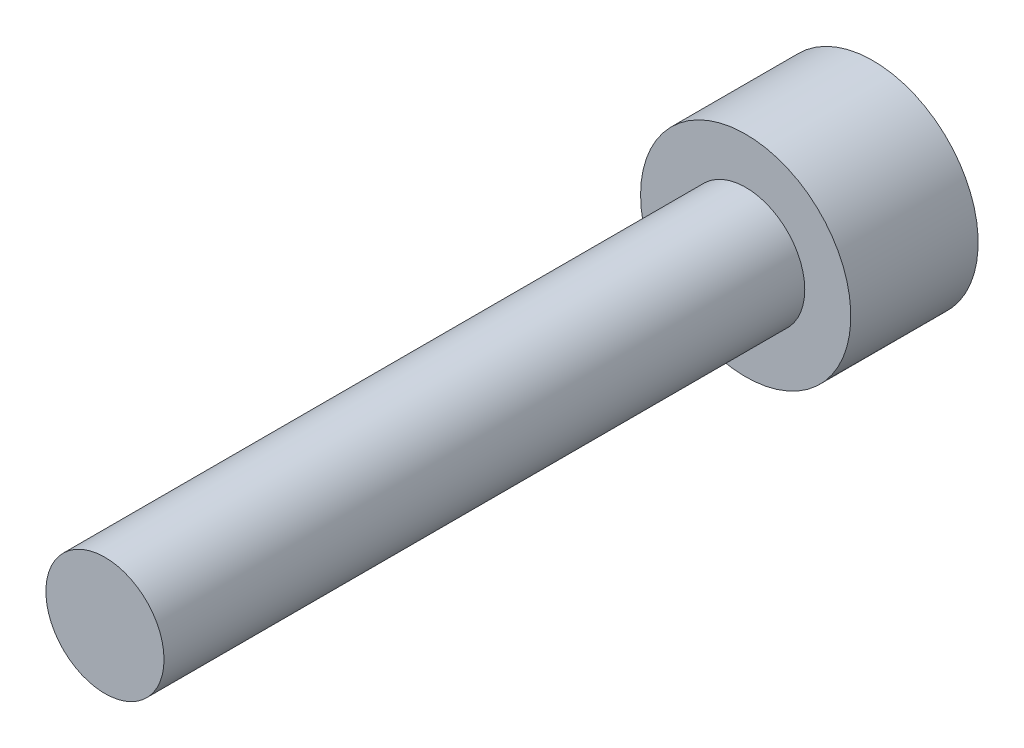
SolidWorks part; units mm, degrees
ref_plane "Front Plane" through (0, 0, 0) normal (0, 0, 1) x (1, 0, 0)
ref_plane "Top Plane" through (0, 0, 0) normal (0, 1, 0) x (1, 0, 0)
ref_plane "Right Plane" through (0, 0, 0) normal (1, 0, 0) x (0, 0, -1)
sketch "Sketch1" plane through (0, 0, 0) normal (0, 0, 1) x (1, 0, 0)
  circle A0 centre (0, 0) radius 2.625
  dimension "D1" = 5.25
extrude "Boss-Extrude1" add sketch "Sketch1" along normal blind 3.18 contours A0
sketch "Sketch2" plane through (0, 0, 3.18) normal (0, 0, 1) x (1, 0, 0)
  circle A0 centre (0, 0) radius 1.475
  dimension "D1" = 2.95
extrude "Boss-Extrude2" add sketch "Sketch2" along normal blind 16
